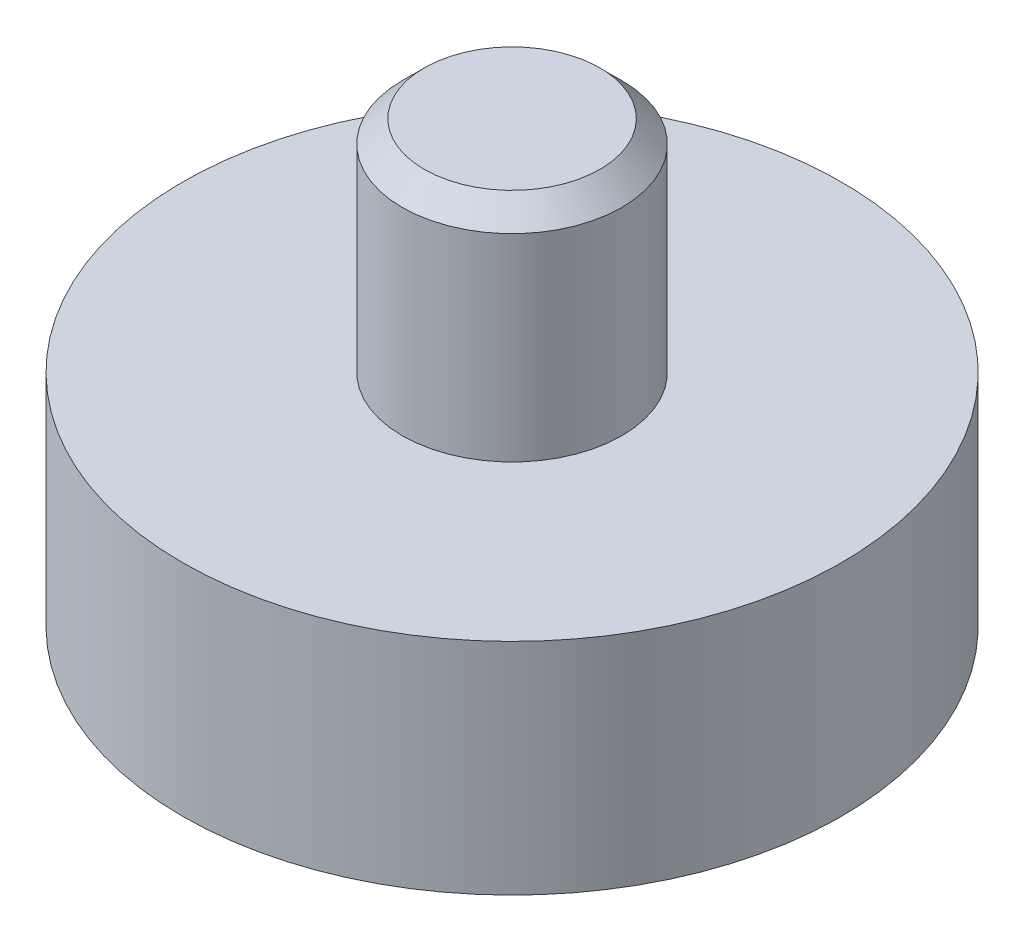
SolidWorks part; units mm, degrees
ref_plane "Front Plane" through (0, 0, 0) normal (0, 0, 1) x (1, 0, 0)
ref_plane "Top Plane" through (0, 0, 0) normal (0, 1, 0) x (1, 0, 0)
ref_plane "Right Plane" through (0, 0, 0) normal (1, 0, 0) x (0, 0, -1)
sketch "Sketch1" plane through (0, 0, 0) normal (0, 1, 0) x (1, 0, 0)
  circle A0 centre (-48.851, 48.1678) radius 15
  dimension "D1" = 30
extrude "Boss-Extrude1" add sketch "Sketch1" along normal blind 10
sketch "Sketch2" plane through (0, 10, 0) normal (0, 1, 0) x (1, 0, 0)
  circle A0 centre (-48.851, 48.1678) radius 5
  dimension "D1" = 10
extrude "Boss-Extrude2" add sketch "Sketch2" along normal blind 10
chamfer "Chamfer1" distance 1 angle 45 1 edges at (-48.851, 20, -43.1678)
